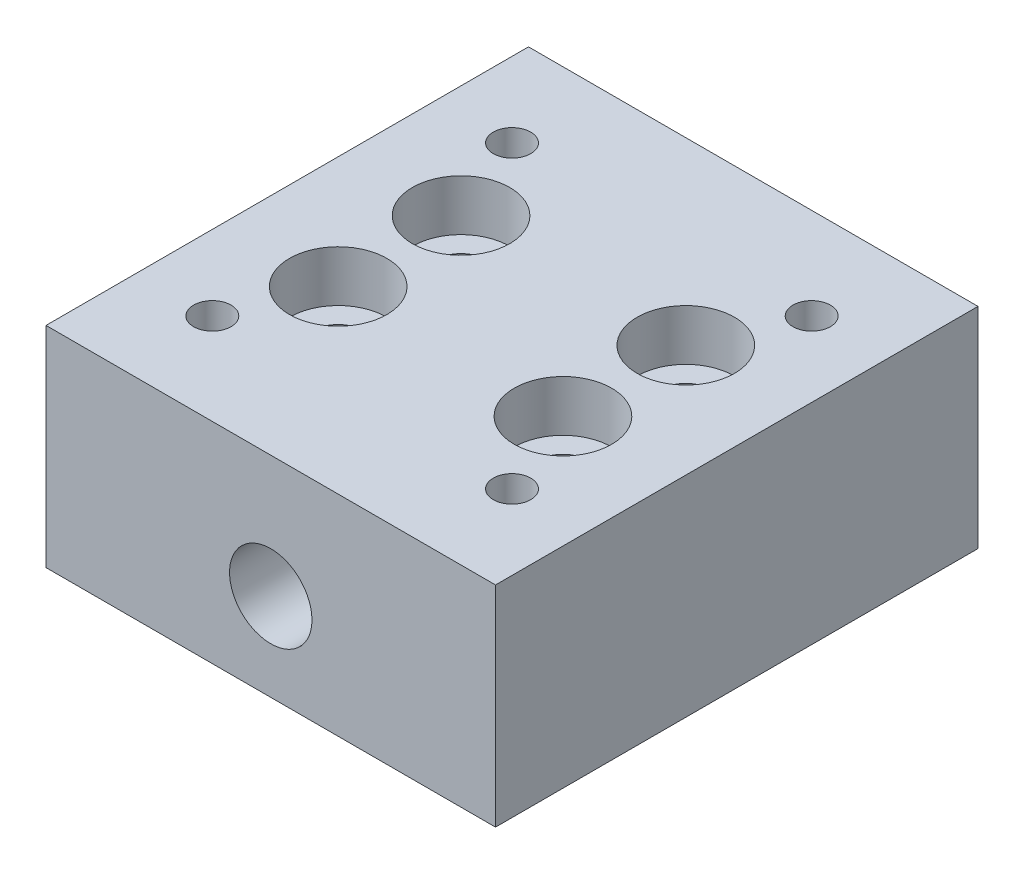
SolidWorks part; units mm, degrees
ref_plane "Спереди" through (0, 0, 0) normal (0, 0, 1) x (1, 0, 0)
ref_plane "Сверху" through (0, 0, 0) normal (0, 1, 0) x (1, 0, 0)
ref_plane "Справа" through (0, 0, 0) normal (1, 0, 0) x (0, 0, -1)
ref_plane "Плоскость4" through (0, 11.5, 0) normal (0, 1, 0) x (1, 0, 0)
sketch "Эскиз1" plane through (0, 11.5, 0) normal (0, 1, 0) x (1, 0, 0)
  line L0 (0, -1315.9954) -> (0, 64483.7766) construction
  line L2 (-15, -26.0506) -> (15, -26.0506)
  line L3 (-15, -26.0506) -> (-15, -58.2506)
  line L4 (-15, -58.2506) -> (15, -58.2506)
  line L5 (15, -26.0506) -> (15, -58.2506)
  dimension "D1" = 32.2
  dimension "D2" = 30
extrude "Body" add sketch "Эскиз1" along normal blind 14
sketch "Эскиз2" plane through (0, 25.5, 0) normal (0, 1, 0) x (1, 0, 0)
  line L0 (0, -58.2506) -> (0, -26.0506) construction
  line L1 (15, -26.0506) -> (-15, -26.0506) construction
  line L2 (-15, -42.1506) -> (15, -42.1506) construction
  line L3 (-15, -26.0506) -> (-15, -58.2506) construction
  line L4 (15, -58.2506) -> (15, -26.0506) construction
  point P0 (-7.5, -38.0506)
  point P1 (7.5, -38.0506)
  point P15 (-7.5, -46.2506)
  point P16 (7.5, -46.2506)
  point P20 (0, -26.0506)
  dimension "D1" = 15
  dimension "D2" = 12
hole_wizard "Fixture M3" positions "Трехмерный эскиз1" profile "Эскиз3" counterbore size "M3" standard "ISO"
sketch3d "Трехмерный эскиз1"
  point P0 (-7.5, 25.5, 38.0506)
  point P3 (-7.5, 25.5, 46.2506)
  point P6 (7.5, 25.5, 38.0506)
  point P9 (7.5, 25.5, 46.2506)
sketch "Эскиз3" plane through (-7.5, 25.5, 38.0506) normal (1, 0, 0) x (0, 0, 1)
  line L0 (0, 0) -> (0, 15.0215)
  line L1 (0, 15.0215) -> (1.7, 14)
  line L2 (1.7, 14) -> (1.7, 3.4)
  line L3 (1.7, 3.4) -> (3.25, 3.4)
  line L4 (3.25, 3.4) -> (3.25, 0)
  line L5 (3.25, 0) -> (0, 0)
  line L10 (0, 15.0215) -> (-1.7, 14) construction
  line L11 (0, -6.35) -> (0, 107.95) construction
  dimension "Диаметр отверстия" = 3.4
  dimension "Глубина отверстия" = 14
  dimension "Диаметр цековки" = 6.5
  dimension "Глубина цековки" = 3.4
  dimension "Угол заточки сверла" = 118
sketch "Эскиз4" plane through (0, 25.5, 0) normal (0, 1, 0) x (1, 0, 0)
  line L0 (0, -58.2506) -> (0, -26.0506) construction
  line L1 (0, -58.2506) -> (0, -26.0506) construction
  line L2 (-15, -42.1506) -> (15, -42.1506) construction
  line L3 (-15, -42.1506) -> (15, -42.1506) construction
  point P0 (-10, -32.1506)
  point P1 (10, -32.1506)
  point P2 (10, -52.1506)
  point P3 (-10, -52.1506)
  dimension "D1" = 20
  dimension "D2" = 20
hole_wizard "Fixture M3_1" positions "Трехмерный эскиз2" profile "Эскиз5" tap size "M3" standard "ISO"
sketch3d "Трехмерный эскиз2"
  point P0 (-10, 25.5, 32.1506)
  point P6 (10, 25.5, 32.1506)
  point P9 (10, 25.5, 52.1506)
  point P12 (-10, 25.5, 52.1506)
sketch "Эскиз5" plane through (-10, 25.5, 32.1506) normal (1, 0, 0) x (0, 0, 1)
  line L0 (0, 0) -> (0, 9.2511)
  line L1 (0, 9.2511) -> (1.25, 8.5)
  line L2 (1.25, 8.5) -> (1.25, 0)
  line L5 (1.25, 0) -> (0, 0)
  line L10 (0, 9.2511) -> (-1.25, 8.5) construction
  line L11 (0, -6.35) -> (0, 107.95) construction
  dimension "Диаметр сверла" = 2.5
  dimension "Глубина сверла" = 8.5
  dimension "Угол заточки сверла" = 118
cosmetic thread "Отверстие резьбы5" parameters "D1"=6, "D2"=3.5
cosmetic thread "Отверстие резьбы6" parameters "D1"=6, "D2"=3.5
cosmetic thread "Отверстие резьбы7" parameters "D1"=6, "D2"=3.5
cosmetic thread "Отверстие резьбы8" parameters "D1"=6, "D2"=3.5
sketch "Эскиз6" plane through (0, 0, 58.2506) normal (0, 0, 1) x (1, 0, 0)
  line L4 (-15, 25.5) -> (15, 25.5) construction
  line L5 (0, 25.5) -> (0, 11.5) construction
  line L6 (55, 11.5) -> (-55, 11.5) construction
  circle A2 centre (0, 17.35) radius 2.75
  dimension "D1" = 5.5
  dimension "D2" = 5.85
extrude "Hole" cut sketch "Эскиз6" against normal up to surface (32.2 mm away) up to face at (0, 18.5, 26.0506)
sketch "Эскиз7" plane through (0, 0, 26.0506) normal (0, 0, -1) x (-1, 0, 0)
  line L0 (-2.5, 17.35) -> (2.5, 17.35) construction
  line L1 (-2.5, 22.35) -> (2.5, 22.35)
  line L5 (-2.5, 12.35) -> (2.5, 12.35)
  arc A7 (-2.5, 22.35) -> (-2.5, 12.35) centre (-2.5, 17.35) ccw
  arc A8 (2.5, 12.35) -> (2.5, 22.35) centre (2.5, 17.35) ccw
  point P3 (0, 17.35)
  dimension "D1" = 5
  dimension "D2" = 10
extrude "Oval" cut sketch "Эскиз7" against normal blind 6
sketch "Эскиз8" plane through (0, 0, 26.0506) normal (0, 0, -1) x (-1, 0, 0)
  circle A2 centre (0, 17.35) radius 2.75 construction
  circle A4 centre (0, 17.35) radius 5
  dimension "D2" = 10
extrude "Hole2" cut sketch "Эскиз8" against normal blind 22
